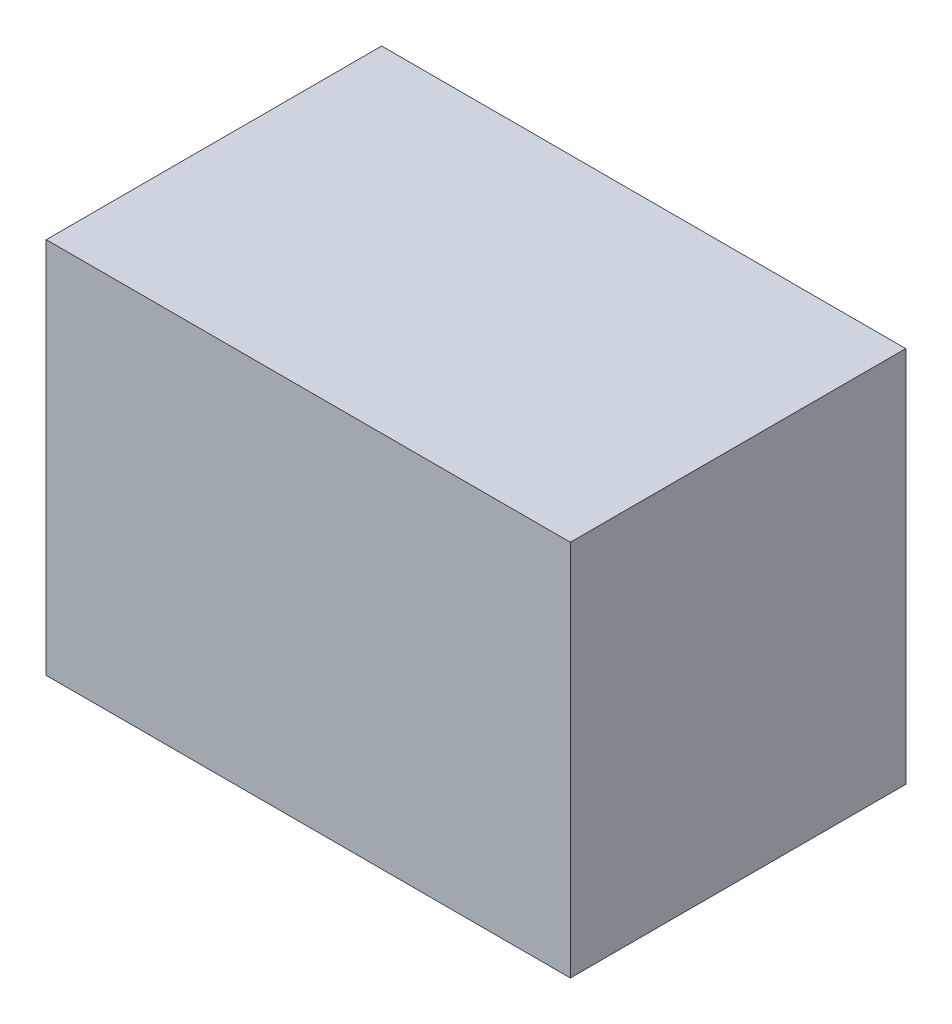
SolidWorks part; units mm, degrees
ref_plane "Front Plane" through (0, 0, 0) normal (0, 0, 1) x (1, 0, 0)
ref_plane "Top Plane" through (0, 0, 0) normal (0, 1, 0) x (1, 0, 0)
ref_plane "Right Plane" through (0, 0, 0) normal (1, 0, 0) x (0, 0, -1)
sketch "Sketch1" plane through (0, 0, 0) normal (0, 1, 0) x (1, 0, 0)
  line L1 (-62.5, -40) -> (62.5, -40)
  line L2 (-62.5, -40) -> (-62.5, 40)
  line L3 (-62.5, 40) -> (62.5, 40)
  line L4 (62.5, -40) -> (62.5, 40)
  line L5 (-62.5, -40) -> (62.5, 40) construction
  line L6 (-62.5, 40) -> (62.5, -40) construction
  point P0 (0, 0)
  dimension "D1" = 125
  dimension "D2" = 80
extrude "Boss-Extrude1" add sketch "Sketch1" along normal blind 90
